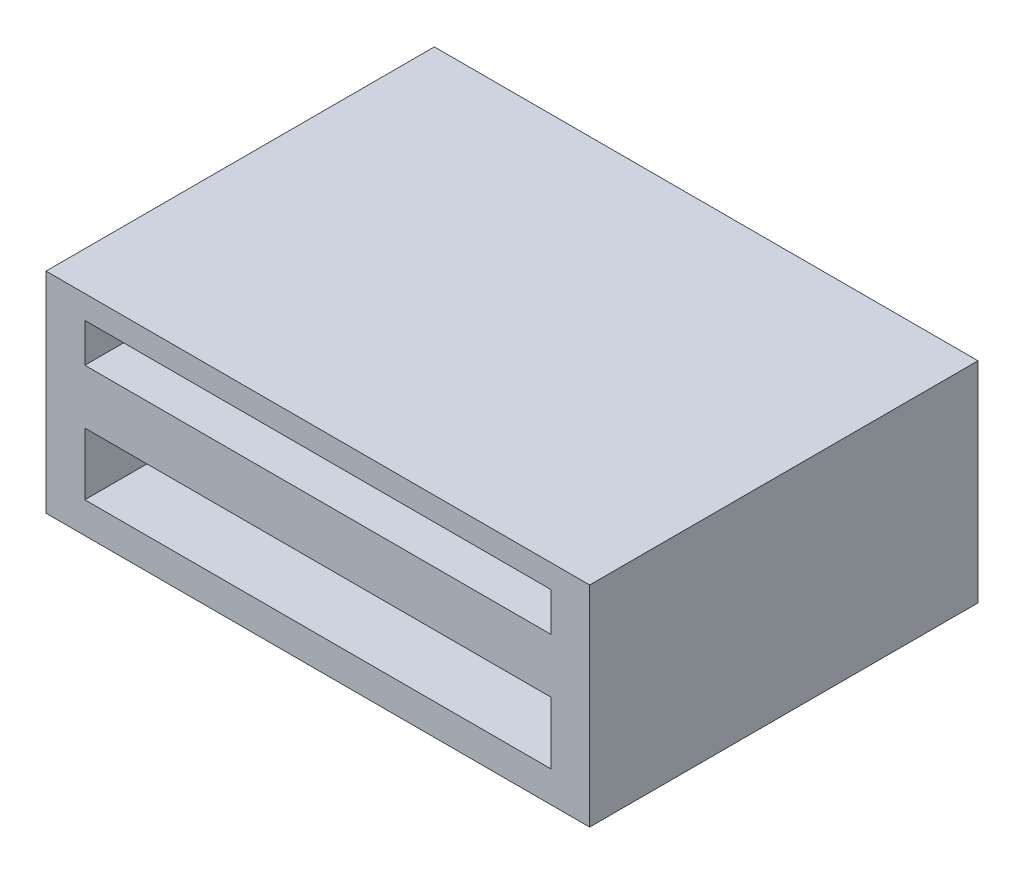
SolidWorks part; units mm, degrees
material "Plain Carbon Steel"
ref_plane "Front Plane" through (0, 0, 0) normal (0, 0, 1) x (1, 0, 0)
ref_plane "Top Plane" through (0, 0, 0) normal (0, 1, 0) x (1, 0, 0)
ref_plane "Right Plane" through (0, 0, 0) normal (1, 0, 0) x (0, 0, -1)
sketch "Sketch2" plane through (0, 0, 0) normal (0, 0, 1) x (1, 0, 0)
  line L1 (0, 0) -> (70, 0)
  line L2 (0, 0) -> (0, 27)
  line L3 (0, 27) -> (70, 27)
  line L4 (70, 0) -> (70, 27)
  line L5 (5, 4) -> (65, 4)
  line L6 (5, 4) -> (5, 12)
  line L7 (5, 12) -> (65, 12)
  line L8 (65, 4) -> (65, 12)
  line L9 (5, 19) -> (65, 19)
  line L10 (5, 19) -> (5, 24)
  line L11 (5, 24) -> (65, 24)
  line L12 (65, 19) -> (65, 24)
  dimension "D1" = 60
  dimension "D2" = 4
  dimension "D3" = 5
  dimension "D4" = 5
  dimension "D5" = 19
  dimension "D6" = 8
  dimension "D7" = 3
  dimension "D8" = 5
extrude "Boss-Extrude1" add sketch "Sketch2" along normal blind 50
